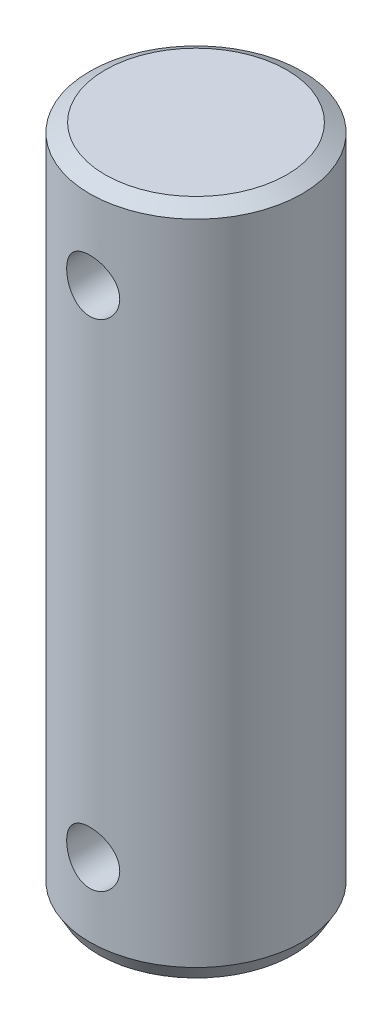
SolidWorks part; units mm, degrees
ref_plane "Front Plane" through (0, 0, 0) normal (0, 0, 1) x (1, 0, 0)
ref_plane "Top Plane" through (0, 0, 0) normal (0, 1, 0) x (1, 0, 0)
ref_plane "Right Plane" through (0, 0, 0) normal (1, 0, 0) x (0, 0, -1)
sketch "Sketch1" plane through (0, 0, 0) normal (0, 1, 0) x (1, 0, 0)
  circle A0 centre (0, 0) radius 6
  dimension "D1" = 12
extrude "Boss-Extrude1" add sketch "Sketch1" along normal mid plane 38
chamfer "Chamfer1" distance 0.5 angle 60 2 edges at (0, -19, 6) (0, 19, 6)
sketch "Sketch2" plane through (0, 0, 0) normal (0, 0, 1) x (1, 0, 0)
  line L0 (5.134, 19) -> (-5.134, 19) construction
  circle A0 centre (0, 14) radius 1.5
  circle A1 centre (0, -14) radius 1.5
  point P2 (0, 0)
  point P7 (0, 0)
  point P8 (0, 0)
  point P11 (0, 0)
  point P12 (0, 0)
  point P13 (0, 0)
  point P14 (0, 0)
  point P15 (0, 0)
  point P16 (0, 0)
  point P17 (0, 0)
  point P18 (0, 0)
  point P19 (0, 0)
  point P20 (0, 0)
  point P21 (0, 0)
  point P22 (0, 0)
  point P23 (0, 0)
  dimension "D1" = 3
  dimension "D2" = 3
  dimension "D3" = 5
extrude "Cut-Extrude1" cut sketch "Sketch2" against normal mid plane 48
